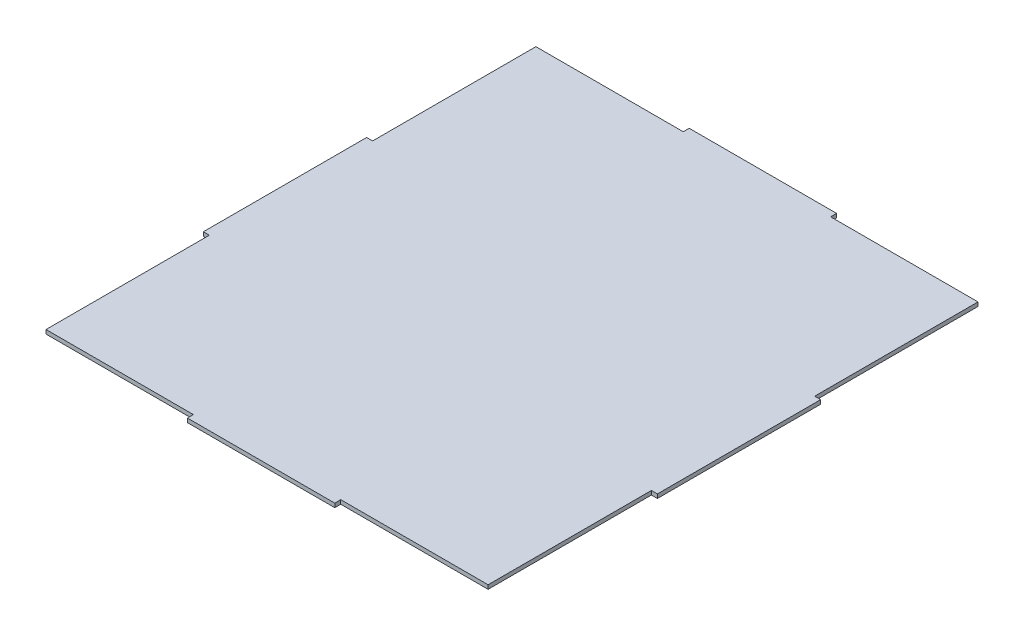
SolidWorks part; units mm, degrees
ref_plane "Front Plane" through (0, 0, 0) normal (0, 0, 1) x (1, 0, 0)
ref_plane "Top Plane" through (0, 0, 0) normal (0, 1, 0) x (1, 0, 0)
ref_plane "Right Plane" through (0, 0, 0) normal (1, 0, 0) x (0, 0, -1)
sketch "Sketch1" plane through (0, 0, 0) normal (0, 1, 0) x (1, 0, 0)
  line L0 (37, 123) -> (111, 123)
  line L1 (-111, -123) -> (-37, -123)
  line L2 (-111, -123) -> (-111, -41)
  line L3 (-111, 123) -> (-37, 123)
  line L4 (111, -123) -> (111, -41)
  line L5 (-111, -123) -> (111, 123) construction
  line L6 (-111, 123) -> (111, -123) construction
  line L7 (111, 41) -> (111, 123)
  line L8 (-37, 123) -> (-37, 126)
  line L9 (-37, 126) -> (37, 126)
  line L10 (37, 123) -> (37, 126)
  line L11 (111, -41) -> (114, -41)
  line L12 (37, -123) -> (111, -123)
  line L13 (111, 41) -> (114, 41)
  line L14 (114, -41) -> (114, 41)
  line L15 (-111, 41) -> (-111, 123)
  line L16 (-37, -123) -> (-37, -126)
  line L17 (-37, -126) -> (37, -126)
  line L18 (37, -123) -> (37, -126)
  line L19 (-111, 41) -> (-114, 41)
  line L21 (-111, -41) -> (-114, -41)
  line L22 (-114, 41) -> (-114, -41)
  point P0 (0, 0)
  dimension "D1" = 246
  dimension "D2" = 222
  dimension "D3" = 3
extrude "Boss-Extrude1" add sketch "Sketch1" along normal blind 2
equation "\"Resolution Projector X\"= 1920"
equation "\"Resolution Projector Y\"= 1080"
equation "\"Resolution Build\"= 0.1"
equation "\"Size Build Volume X\"= \"Resolution Projector X\" * \"Resolution Build\""
equation "\"Size Build Volume Y\"= 2 * \"Resolution Projector Y\" * \"Resolution Build\""
equation "\"Size Build Volume Z\"= \"Size Build Volume Y\""
equation "\"Thick\"= 0.125in"
equation "\"Size Enclosure Internal X\"= 350mm"
equation "\"Size Enclosure Internal Y\"= \"Size Enclosure Internal X\""
equation "\"Size Enclosure Internal Z\"= \"Size Enclosure Internal X\""
equation "\"Size Enclosure External Z\"= 1000mm"
equation "\"Diameter Screw\"= 3mm"
equation "\"Diameter Nut\"= 5.5mm"
equation "\"Thick Nut\"= 2.5mm"
equation "\"Length Screw\"= 12mm"
equation "\"D1@Sketch1\"=\"Size Build Volume Y\" + 30"
equation "\"D2@Sketch1\"=\"Size Build Volume X\"+30"
